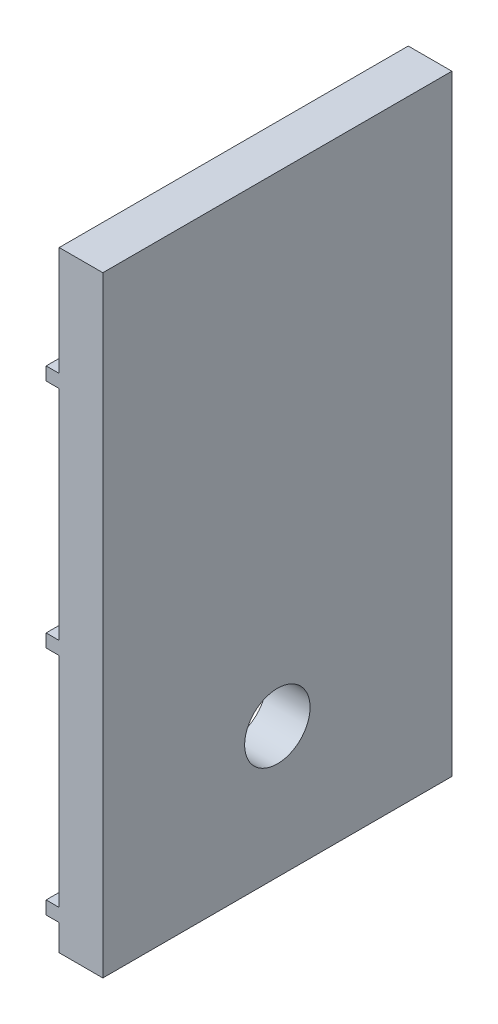
SolidWorks part; units mm, degrees
ref_plane "Front Plane" through (0, 0, 0) normal (0, 0, 1) x (1, 0, 0)
ref_plane "Top Plane" through (0, 0, 0) normal (0, 1, 0) x (1, 0, 0)
ref_plane "Right Plane" through (0, 0, 0) normal (1, 0, 0) x (0, 0, -1)
sketch "Sketch1" plane through (0, 0, 0) normal (0, 0, 1) x (1, 0, 0)
  line L0 (-10.1087, -78.6286) -> (-10.1087, 61.3714)
  line L1 (-10.1087, 61.3714) -> (-20.1087, 61.3714)
  line L2 (-20.1087, 61.3714) -> (-20.1087, 36.3714)
  line L3 (-20.1087, 36.3714) -> (-23.1087, 36.3714)
  line L4 (-23.1087, 36.3714) -> (-23.1087, 33.3714)
  line L5 (-23.1087, 33.3714) -> (-20.1087, 33.3714)
  line L6 (-20.1087, 33.3714) -> (-20.1087, -16.6286)
  line L7 (-20.1087, -16.6286) -> (-23.1087, -16.6286)
  line L8 (-23.1087, -16.6286) -> (-23.1087, -19.6286)
  line L9 (-23.1087, -19.6286) -> (-20.1087, -19.6286)
  line L10 (-20.1087, -19.6286) -> (-20.1087, -69.6286)
  line L11 (-20.1087, -69.6286) -> (-23.1087, -69.6286)
  line L12 (-23.1087, -69.6286) -> (-23.1087, -72.6286)
  line L13 (-23.1087, -72.6286) -> (-20.1087, -72.6286)
  line L14 (-20.1087, -72.6286) -> (-20.1087, -78.6286)
  line L15 (-20.1087, -78.6286) -> (-10.1087, -78.6286)
  dimension "D1" = 140
  dimension "D2" = 25
  dimension "D3" = 3
  dimension "D4" = 3
  dimension "D5" = 3
  dimension "D6" = 10
  dimension "D7" = 10
  dimension "D8" = 50
  dimension "D9" = 3
  dimension "3" = 3
  dimension "D10" = 50
  dimension "D11" = 3
  dimension "D12" = 3
  dimension "D13" = 3
extrude "Boss-Extrude1" add sketch "Sketch1" along normal blind 80
sketch "Sketch2" plane through (-20.1087, 0, 0) normal (-1, 0, 0) x (0, 0, 1)
  line L1 (80, -69.6286) -> (0, -69.6286) construction
  line L2 (80, -19.6286) -> (80, -69.6286) construction
  circle A0 centre (40, -48.6286) radius 7.5
  dimension "D1" = 15
  dimension "D2" = 21
  dimension "D3" = 40
extrude "Cut-Extrude1" cut sketch "Sketch2" against normal blind 80
